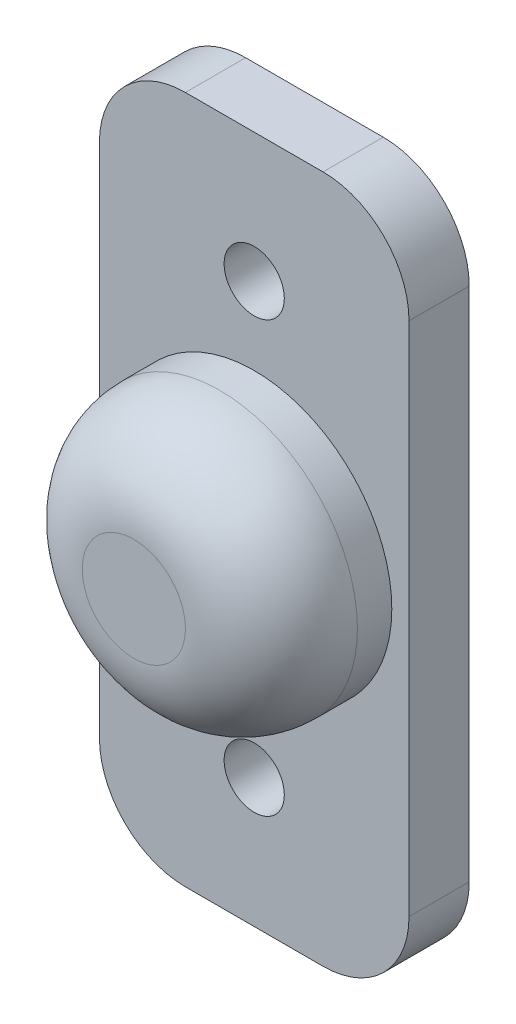
SolidWorks part; units mm, degrees
ref_plane "Front Plane" through (0, 0, 0) normal (0, 0, 1) x (1, 0, 0)
ref_plane "Top Plane" through (0, 0, 0) normal (0, 1, 0) x (1, 0, 0)
ref_plane "Right Plane" through (0, 0, 0) normal (1, 0, 0) x (0, 0, -1)
sketch "Sketch1" plane through (0, 0, 0) normal (0, 0, 1) x (1, 0, 0)
  line L0 (-6.9703, 28.8141) -> (-6.9703, -11.1859) construction
  line L1 (-15.9703, 28.8141) -> (2.0297, 28.8141)
  line L2 (-15.9703, 28.8141) -> (-15.9703, -11.1859)
  line L3 (-15.9703, -11.1859) -> (2.0297, -11.1859)
  line L4 (2.0297, 28.8141) -> (2.0297, -11.1859)
  circle A0 centre (-6.9703, 21.3141) radius 1.75
  circle A1 centre (-6.9703, -3.6859) radius 1.75
  dimension "D3" = 3.5
  dimension "D4" = 7.5
  dimension "D5" = 7.5
  dimension "D1" = 18
  dimension "D2" = 40
extrude "Boss-Extrude1" add sketch "Sketch1" along normal blind 3.5
sketch "Sketch2" plane through (0, 0, 3.5) normal (0, 0, 1) x (1, 0, 0)
  line L0 (-6.9703, 28.8141) -> (-6.9703, -11.1859) construction
  line L1 (2.0297, 28.8141) -> (-15.9703, 28.8141) construction
  line L2 (-15.9703, -11.1859) -> (2.0297, -11.1859) construction
  circle A0 centre (-6.9703, 8.8141) radius 8
  dimension "D1" = 16
extrude "Boss-Extrude2" add sketch "Sketch2" along normal blind 7
sketch "Sketch3" plane through (0, 0, 0) normal (0, 0, -1) x (-1, 0, 0)
  circle A0 centre (6.9703, 8.8141) radius 5
  dimension "D1" = 10
extrude "Cut-Extrude1" cut sketch "Sketch3" against normal offset from surface (6.5 mm away) 4 up to face at (1.0297, 8.8141, 10.5)
fillet "Fillet1" radius 5 5 edges at (1.0297, 8.8141, 10.5) (2.0297, -11.1859, 1.75) (-15.9703, -11.1859, 1.75) (-15.9703, 28.8141, 1.75) (2.0297, 28.8141, 1.75)
ref_point "Point1"
